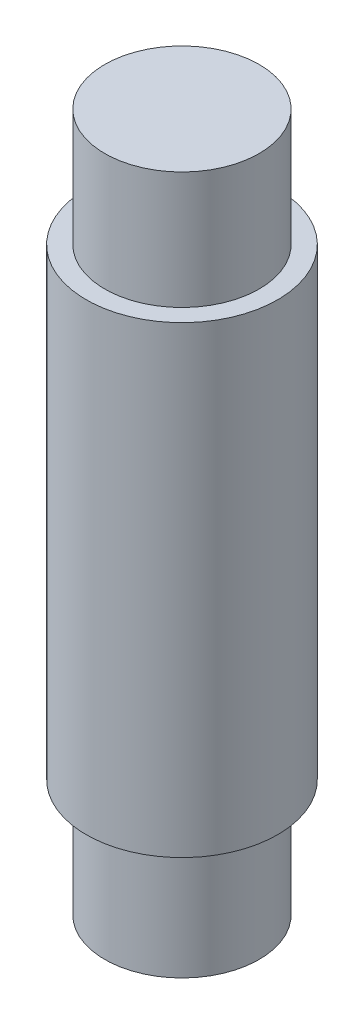
SolidWorks part; units mm, degrees
ref_plane "Front Plane" through (0, 0, 0) normal (0, 0, 1) x (1, 0, 0)
ref_plane "Top Plane" through (0, 0, 0) normal (0, 1, 0) x (1, 0, 0)
ref_plane "Right Plane" through (0, 0, 0) normal (1, 0, 0) x (0, 0, -1)
sketch "Sketch1" plane through (0, 0, 0) normal (0, 0, 1) x (1, 0, 0)
  line L0 (0, 0) -> (0, -4.826)
  line L1 (0, -4.826) -> (0.762, -4.826)
  line L2 (0.762, -4.826) -> (0.762, -23.876)
  line L3 (0.762, -23.876) -> (0, -23.876)
  line L4 (0, -23.876) -> (0, -28.702)
  line L5 (0, -28.702) -> (-3.175, -28.702)
  line L6 (-3.175, -28.702) -> (-3.175, 0)
  line L7 (-3.175, 0) -> (0, 0)
  dimension "D1" = 4.826
  dimension "D2" = 19.05
  dimension "D3" = 3.175
  dimension "D4" = 3.937
revolve "Revolve1" add sketch "Sketch1" angle 360 about L6
